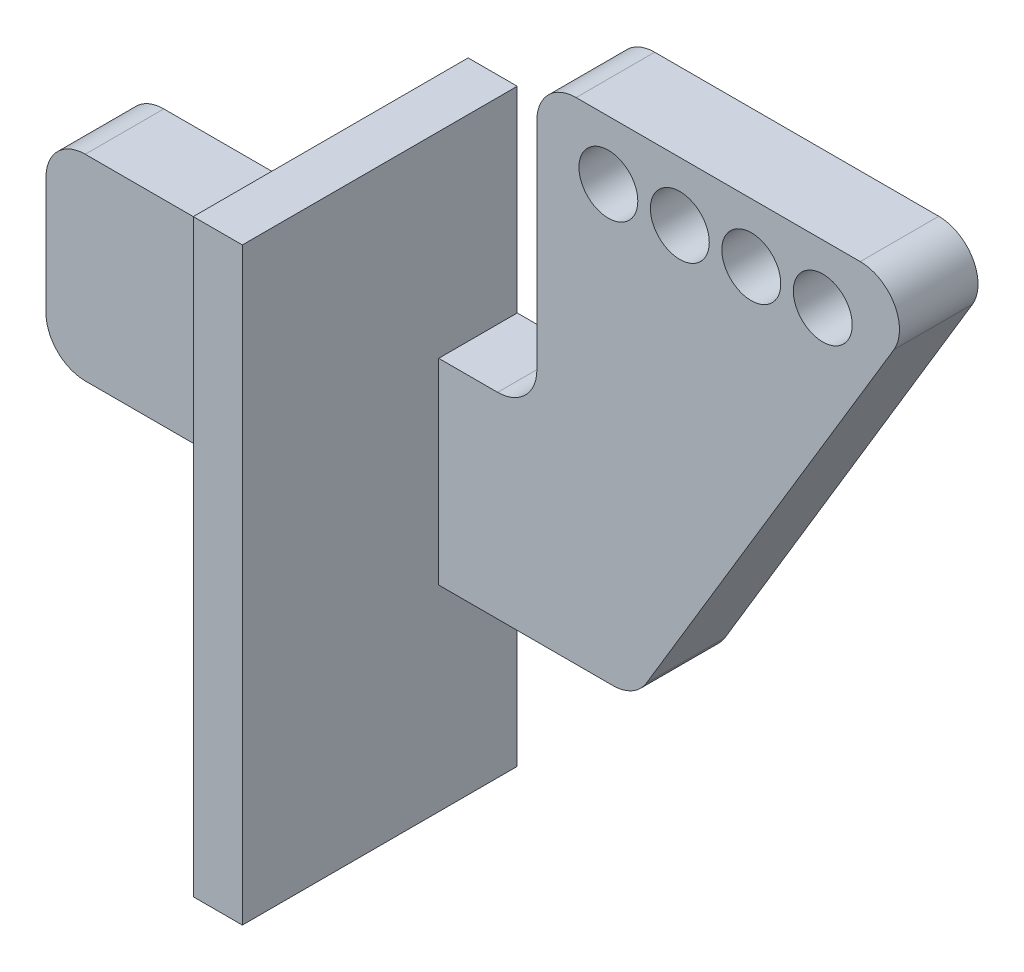
SolidWorks part; units mm, degrees
ref_plane "Plan de face" through (0, 0, 0) normal (0, 0, 1) x (1, 0, 0)
ref_plane "Plan de dessus" through (0, 0, 0) normal (0, 1, 0) x (1, 0, 0)
ref_plane "Plan de droite" through (0, 0, 0) normal (1, 0, 0) x (0, 0, -1)
sketch "Esquisse1" plane through (0, 0, 0) normal (0, 0, 1) x (1, 0, 0)
  line L0 (0, 0) -> (0, 15)
  line L1 (0, 15) -> (20, 15)
  line L2 (20, 15) -> (5, -10)
  line L3 (5, -10) -> (-25, -10) construction
  line L4 (-25, -10) -> (-25, 0)
  line L5 (-25, 0) -> (0, 0) construction
  line L6 (0, 0) -> (-5, 0)
  line L7 (-5, 0) -> (-5, 10)
  line L8 (-5, 10) -> (-7.5, 10)
  line L9 (-7.5, 10) -> (-7.5, 0)
  line L10 (-7.5, 0) -> (-25, 0)
  line L11 (-25, -10) -> (-7.5, -10)
  line L12 (-7.5, -10) -> (-7.5, -20)
  line L13 (-7.5, -20) -> (-5, -20)
  line L14 (-5, -20) -> (-5, -10)
  line L15 (-5, -10) -> (5, -10)
  line L17 (3.64, 12) -> (7.28, 12) construction
  line L18 (7.28, 12) -> (10.92, 12) construction
  line L19 (10.92, 12) -> (14.56, 12) construction
  line L20 (14.56, 12) -> (18.2, 12) construction
  line L21 (3.64, 12) -> (0, 12) construction
  circle A0 centre (3.64, 12) radius 1.5
  circle A1 centre (7.28, 12) radius 1.5
  circle A2 centre (10.92, 12) radius 1.5
  circle A3 centre (14.56, 12) radius 1.5
extrude "Boss.-Extru.1" add sketch "Esquisse1" along normal blind 4
sketch "Esquisse2" plane through (0, 0, 4) normal (0, 0, 1) x (1, 0, 0)
  line L1 (-7.5, 10) -> (-5, 10)
  line L2 (-7.5, 10) -> (-7.5, -20)
  line L3 (-7.5, -20) -> (-5, -20)
  line L4 (-5, 10) -> (-5, -20)
extrude "Boss.-Extru.2" add sketch "Esquisse2" along normal blind 10
fillet "Congé1" radius 2 6 edges at (-25, -10, 2) (-25, 0, 2) (0, 0, 2) (0, 15, 2) (20, 15, 2) (5, -10, 2)
